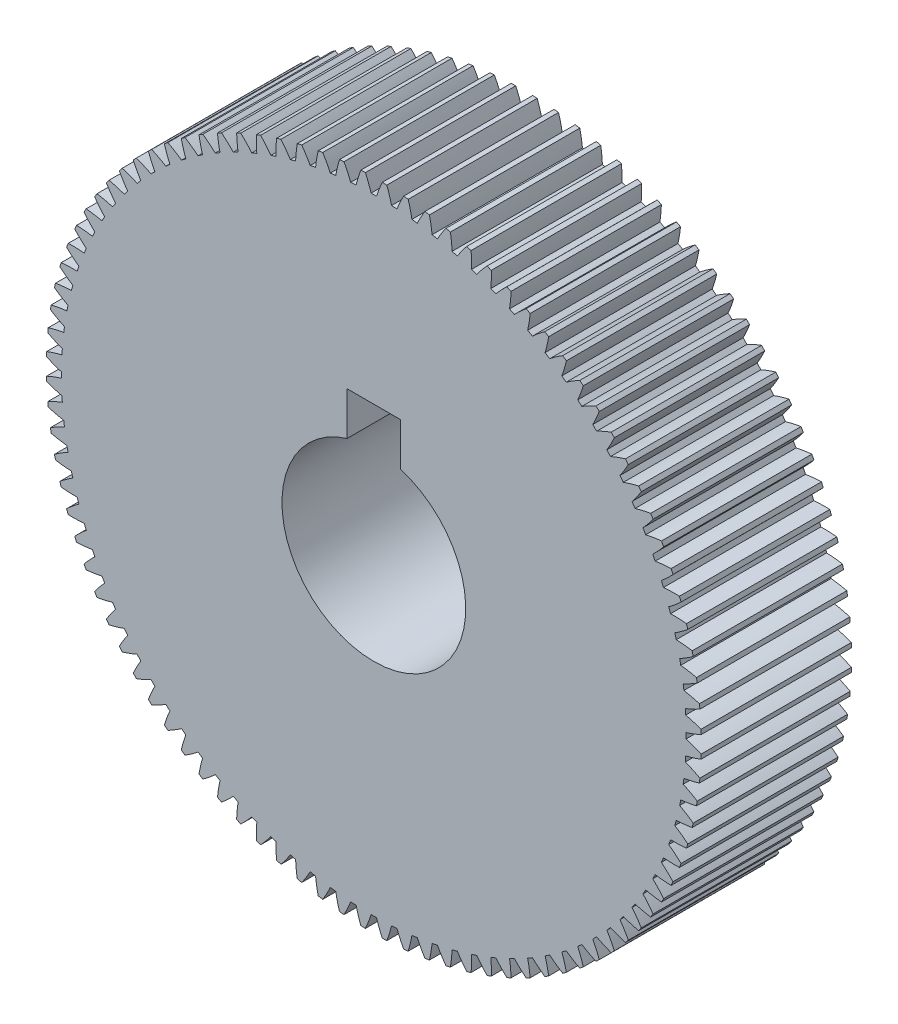
SolidWorks part; units mm, degrees
ref_plane "前视基准面" through (0, 0, 0) normal (0, 0, 1) x (1, 0, 0)
ref_plane "上视基准面" through (0, 0, 0) normal (0, 1, 0) x (1, 0, 0)
ref_plane "右视基准面" through (0, 0, 0) normal (1, 0, 0) x (0, 0, -1)
sketch "Model" plane through (0, 0, 0) normal (0, 0, 1) x (1, 0, 0)
  line L0 (6, 19.0788) -> (6, 23.3)
  line L1 (-6, 23.3) -> (-6, 19.0788)
  line L2 (6, 23.3) -> (-6, 23.3)
  arc A0 (-97.9675, 2.5241) -> (-93.4954, 0.8163) centre (-82.0589, 37.4737) ccw
  arc A1 (-93.4954, 0.8163) -> (-93.4954, -0.8163) centre (0, 0) ccw
  arc A2 (-93.4954, -0.8163) -> (-97.9675, -2.5241) centre (-82.0589, -37.4737) ccw
  arc A3 (-97.9675, -2.5241) -> (-97.9228, -3.8887) centre (0, 0) ccw
  arc A4 (-97.9228, -3.8887) -> (-93.3486, -5.3003) centre (-84.3341, 32.0266) ccw
  arc A5 (-93.3486, -5.3003) -> (-93.2419, -6.9294) centre (0, 0) ccw
  arc A6 (-93.2419, -6.9294) -> (-97.5927, -8.9261) centre (-79.4323, -42.7604) ccw
  arc A7 (-97.5927, -8.9261) -> (-97.4588, -10.2848) centre (0, 0) ccw
  arc A8 (-97.4588, -10.2848) -> (-92.8021, -11.3943) centre (-86.2481, 26.4423) ccw
  arc A9 (-92.8021, -11.3943) -> (-92.589, -13.0129) centre (0, 0) ccw
  arc A10 (-92.589, -13.0129) -> (-96.7999, -15.2898) centre (-76.4655, -47.8639) ccw
  arc A11 (-96.7999, -15.2898) -> (-96.5775, -16.6369) centre (0, 0) ccw
  arc A12 (-96.5775, -16.6369) -> (-91.8582, -17.4394) centre (-87.7929, 20.7448) ccw
  arc A13 (-91.8582, -17.4394) -> (-91.5397, -19.0407) centre (0, 0) ccw
  arc A14 (-91.5397, -19.0407) -> (-95.5926, -21.5881) centre (-73.1714, -52.7625) ccw
  arc A15 (-95.5926, -21.5881) -> (-95.2826, -22.9178) centre (0, 0) ccw
  arc A16 (-95.2826, -22.9178) -> (-90.5209, -23.4099) centre (-88.9617, 14.9584) ccw
  arc A17 (-90.5209, -23.4099) -> (-90.0984, -24.9869) centre (0, 0) ccw
  arc A18 (-90.0984, -24.9869) -> (-93.976, -27.7939) centre (-69.5639, -57.4352) ccw
  arc A19 (-93.976, -27.7939) -> (-93.5797, -29.1005) centre (0, 0) ccw
  arc A20 (-93.5797, -29.1005) -> (-88.796, -29.2801) centre (-89.7495, 9.108) ccw
  arc A21 (-88.796, -29.2801) -> (-88.2713, -30.8261) centre (0, 0) ccw
  arc A22 (-88.2713, -30.8261) -> (-91.957, -33.8808) centre (-65.6585, -61.8619) ccw
  arc A23 (-91.957, -33.8808) -> (-91.4761, -35.1586) centre (0, 0) ccw
  arc A24 (-91.4761, -35.1586) -> (-86.6909, -35.025) centre (-90.1531, 3.2186) ccw
  arc A25 (-86.6909, -35.025) -> (-86.0661, -36.5333) centre (0, 0) ccw
  arc A26 (-86.0661, -36.5333) -> (-89.5442, -39.8225) centre (-61.4719, -66.0237) ccw
  arc A27 (-89.5442, -39.8225) -> (-88.9807, -41.0661) centre (0, 0) ccw
  arc A28 (-88.9807, -41.0661) -> (-84.2145, -40.6199) centre (-90.1705, -2.6846) ccw
  arc A29 (-84.2145, -40.6199) -> (-83.4925, -42.0841) centre (0, 0) ccw
  arc A30 (-83.4925, -42.0841) -> (-86.748, -45.5937) centre (-57.0222, -69.9028) ccw
  arc A31 (-86.748, -45.5937) -> (-86.1044, -46.7978) centre (0, 0) ccw
  arc A32 (-86.1044, -46.7978) -> (-81.3776, -46.0408) centre (-89.8019, -8.5763) ccw
  arc A33 (-81.3776, -46.0408) -> (-80.5613, -47.4547) centre (0, 0) ccw
  arc A34 (-80.5613, -47.4547) -> (-83.5803, -51.1697) centre (-52.3282, -73.4826) ccw
  arc A35 (-83.5803, -51.1697) -> (-82.8593, -52.3291) centre (0, 0) ccw
  arc A36 (-82.8593, -52.3291) -> (-78.1921, -51.2646) centre (-89.0487, -14.4312) ccw
  arc A37 (-78.1921, -51.2646) -> (-77.2851, -52.622) centre (0, 0) ccw
  arc A38 (-77.2851, -52.622) -> (-80.0547, -56.5265) centre (-47.4102, -76.7477) ccw
  arc A39 (-80.0547, -56.5265) -> (-79.2594, -57.6363) centre (0, 0) ccw
  arc A40 (-79.2594, -57.6363) -> (-74.6719, -56.2688) centre (-87.9142, -20.2244) ccw
  arc A41 (-74.6719, -56.2688) -> (-73.678, -57.564) centre (0, 0) ccw
  arc A42 (-73.678, -57.564) -> (-76.1863, -61.6413) centre (-42.2891, -79.6841) ccw
  arc A43 (-76.1863, -61.6413) -> (-75.3201, -62.6967) centre (0, 0) ccw
  arc A44 (-75.3201, -62.6967) -> (-70.8318, -61.0321) centre (-86.4032, -25.9309) ccw
  arc A45 (-70.8318, -61.0321) -> (-69.7554, -62.2596) centre (0, 0) ccw
  arc A46 (-69.7554, -62.2596) -> (-71.9916, -66.4922) centre (-36.987, -82.2794) ccw
  arc A47 (-71.9916, -66.4922) -> (-71.0583, -67.4887) centre (0, 0) ccw
  arc A48 (-71.0583, -67.4887) -> (-66.6885, -65.534) centre (-84.5223, -31.5265) ccw
  arc A49 (-66.6885, -65.534) -> (-65.534, -66.6885) centre (0, 0) ccw
  arc A50 (-65.534, -66.6885) -> (-67.4887, -71.0583) centre (-31.5265, -84.5223) ccw
  arc A51 (-67.4887, -71.0583) -> (-66.4922, -71.9916) centre (0, 0) ccw
  arc A52 (-66.4922, -71.9916) -> (-62.2596, -69.7554) centre (-82.2794, -36.987) ccw
  arc A53 (-62.2596, -69.7554) -> (-61.0321, -70.8318) centre (0, 0) ccw
  arc A54 (-61.0321, -70.8318) -> (-62.6967, -75.3201) centre (-25.9309, -86.4032) ccw
  arc A55 (-62.6967, -75.3201) -> (-61.6413, -76.1863) centre (0, 0) ccw
  arc A56 (-61.6413, -76.1863) -> (-57.564, -73.678) centre (-79.6841, -42.2891) ccw
  arc A57 (-57.564, -73.678) -> (-56.2688, -74.6719) centre (0, 0) ccw
  arc A58 (-56.2688, -74.6719) -> (-57.6363, -79.2594) centre (-20.2244, -87.9142) ccw
  arc A59 (-57.6363, -79.2594) -> (-56.5265, -80.0547) centre (0, 0) ccw
  arc A60 (-56.5265, -80.0547) -> (-52.622, -77.2851) centre (-76.7477, -47.4102) ccw
  arc A61 (-52.622, -77.2851) -> (-51.2646, -78.1921) centre (0, 0) ccw
  arc A62 (-51.2646, -78.1921) -> (-52.3291, -82.8593) centre (-14.4312, -89.0487) ccw
  arc A63 (-52.3291, -82.8593) -> (-51.1697, -83.5803) centre (0, 0) ccw
  arc A64 (-51.1697, -83.5803) -> (-47.4547, -80.5613) centre (-73.4826, -52.3282) ccw
  arc A65 (-47.4547, -80.5613) -> (-46.0408, -81.3776) centre (0, 0) ccw
  arc A66 (-46.0408, -81.3776) -> (-46.7978, -86.1044) centre (-8.5763, -89.8019) ccw
  arc A67 (-46.7978, -86.1044) -> (-45.5937, -86.748) centre (0, 0) ccw
  arc A68 (-45.5937, -86.748) -> (-42.0841, -83.4925) centre (-69.9028, -57.0222) ccw
  arc A69 (-42.0841, -83.4925) -> (-40.6199, -84.2145) centre (0, 0) ccw
  arc A70 (-40.6199, -84.2145) -> (-41.0661, -88.9807) centre (-2.6846, -90.1705) ccw
  arc A71 (-41.0661, -88.9807) -> (-39.8225, -89.5442) centre (0, 0) ccw
  arc A72 (-39.8225, -89.5442) -> (-36.5333, -86.0661) centre (-66.0237, -61.4719) ccw
  arc A73 (-36.5333, -86.0661) -> (-35.025, -86.6909) centre (0, 0) ccw
  arc A74 (-35.025, -86.6909) -> (-35.1586, -91.4761) centre (3.2186, -90.1531) ccw
  arc A75 (-35.1586, -91.4761) -> (-33.8808, -91.957) centre (0, 0) ccw
  arc A76 (-33.8808, -91.957) -> (-30.8261, -88.2713) centre (-61.8619, -65.6585) ccw
  arc A77 (-30.8261, -88.2713) -> (-29.2801, -88.796) centre (0, 0) ccw
  arc A78 (-29.2801, -88.796) -> (-29.1005, -93.5797) centre (9.108, -89.7495) ccw
  arc A79 (-29.1005, -93.5797) -> (-27.7939, -93.976) centre (0, 0) ccw
  arc A80 (-27.7939, -93.976) -> (-24.9869, -90.0984) centre (-57.4352, -69.5639) ccw
  arc A81 (-24.9869, -90.0984) -> (-23.4099, -90.5209) centre (0, 0) ccw
  arc A82 (-23.4099, -90.5209) -> (-22.9178, -95.2826) centre (14.9584, -88.9617) ccw
  arc A83 (-22.9178, -95.2826) -> (-21.5881, -95.5926) centre (0, 0) ccw
  arc A84 (-21.5881, -95.5926) -> (-19.0407, -91.5397) centre (-52.7625, -73.1714) ccw
  arc A85 (-19.0407, -91.5397) -> (-17.4394, -91.8582) centre (0, 0) ccw
  arc A86 (-17.4394, -91.8582) -> (-16.6369, -96.5775) centre (20.7448, -87.7929) ccw
  arc A87 (-16.6369, -96.5775) -> (-15.2898, -96.7999) centre (0, 0) ccw
  arc A88 (-15.2898, -96.7999) -> (-13.0129, -92.589) centre (-47.8639, -76.4655) ccw
  arc A89 (-13.0129, -92.589) -> (-11.3943, -92.8021) centre (0, 0) ccw
  arc A90 (-11.3943, -92.8021) -> (-10.2848, -97.4588) centre (26.4423, -86.2481) ccw
  arc A91 (-10.2848, -97.4588) -> (-8.9261, -97.5927) centre (0, 0) ccw
  arc A92 (-8.9261, -97.5927) -> (-6.9294, -93.2419) centre (-42.7604, -79.4323) ccw
  arc A93 (-6.9294, -93.2419) -> (-5.3003, -93.3486) centre (0, 0) ccw
  arc A94 (-5.3003, -93.3486) -> (-3.8887, -97.9228) centre (32.0266, -84.3341) ccw
  arc A95 (-3.8887, -97.9228) -> (-2.5241, -97.9675) centre (0, 0) ccw
  arc A96 (-2.5241, -97.9675) -> (-0.8163, -93.4954) centre (-37.4737, -82.0589) ccw
  arc A97 (-0.8163, -93.4954) -> (0.8163, -93.4954) centre (0, 0) ccw
  arc A98 (0.8163, -93.4954) -> (2.5241, -97.9675) centre (37.4737, -82.0589) ccw
  arc A99 (2.5241, -97.9675) -> (3.8887, -97.9228) centre (0, 0) ccw
  arc A100 (3.8887, -97.9228) -> (5.3003, -93.3486) centre (-32.0266, -84.3341) ccw
  arc A101 (5.3003, -93.3486) -> (6.9294, -93.2419) centre (0, 0) ccw
  arc A102 (6.9294, -93.2419) -> (8.9261, -97.5927) centre (42.7604, -79.4323) ccw
  arc A103 (8.9261, -97.5927) -> (10.2848, -97.4588) centre (0, 0) ccw
  arc A104 (10.2848, -97.4588) -> (11.3943, -92.8021) centre (-26.4423, -86.2481) ccw
  arc A105 (11.3943, -92.8021) -> (13.0129, -92.589) centre (0, 0) ccw
  arc A106 (13.0129, -92.589) -> (15.2898, -96.7999) centre (47.8639, -76.4655) ccw
  arc A107 (15.2898, -96.7999) -> (16.6369, -96.5775) centre (0, 0) ccw
  arc A108 (16.6369, -96.5775) -> (17.4394, -91.8582) centre (-20.7448, -87.7929) ccw
  arc A109 (17.4394, -91.8582) -> (19.0407, -91.5397) centre (0, 0) ccw
  arc A110 (19.0407, -91.5397) -> (21.5881, -95.5926) centre (52.7625, -73.1714) ccw
  arc A111 (21.5881, -95.5926) -> (22.9178, -95.2826) centre (0, 0) ccw
  arc A112 (22.9178, -95.2826) -> (23.4099, -90.5209) centre (-14.9584, -88.9617) ccw
  arc A113 (23.4099, -90.5209) -> (24.9869, -90.0984) centre (0, 0) ccw
  arc A114 (24.9869, -90.0984) -> (27.7939, -93.976) centre (57.4352, -69.5639) ccw
  arc A115 (27.7939, -93.976) -> (29.1005, -93.5797) centre (0, 0) ccw
  arc A116 (29.1005, -93.5797) -> (29.2801, -88.796) centre (-9.108, -89.7495) ccw
  arc A117 (29.2801, -88.796) -> (30.8261, -88.2713) centre (0, 0) ccw
  arc A118 (30.8261, -88.2713) -> (33.8808, -91.957) centre (61.8619, -65.6585) ccw
  arc A119 (33.8808, -91.957) -> (35.1586, -91.4761) centre (0, 0) ccw
  arc A120 (35.1586, -91.4761) -> (35.025, -86.6909) centre (-3.2186, -90.1531) ccw
  arc A121 (35.025, -86.6909) -> (36.5333, -86.0661) centre (0, 0) ccw
  arc A122 (36.5333, -86.0661) -> (39.8225, -89.5442) centre (66.0237, -61.4719) ccw
  arc A123 (39.8225, -89.5442) -> (41.0661, -88.9807) centre (0, 0) ccw
  arc A124 (41.0661, -88.9807) -> (40.6199, -84.2145) centre (2.6846, -90.1705) ccw
  arc A125 (40.6199, -84.2145) -> (42.0841, -83.4925) centre (0, 0) ccw
  arc A126 (42.0841, -83.4925) -> (45.5937, -86.748) centre (69.9028, -57.0222) ccw
  arc A127 (45.5937, -86.748) -> (46.7978, -86.1044) centre (0, 0) ccw
  arc A128 (46.7978, -86.1044) -> (46.0408, -81.3776) centre (8.5763, -89.8019) ccw
  arc A129 (46.0408, -81.3776) -> (47.4547, -80.5613) centre (0, 0) ccw
  arc A130 (47.4547, -80.5613) -> (51.1697, -83.5803) centre (73.4826, -52.3282) ccw
  arc A131 (51.1697, -83.5803) -> (52.3291, -82.8593) centre (0, 0) ccw
  arc A132 (52.3291, -82.8593) -> (51.2646, -78.1921) centre (14.4312, -89.0487) ccw
  arc A133 (51.2646, -78.1921) -> (52.622, -77.2851) centre (0, 0) ccw
  arc A134 (52.622, -77.2851) -> (56.5265, -80.0547) centre (76.7477, -47.4102) ccw
  arc A135 (56.5265, -80.0547) -> (57.6363, -79.2594) centre (0, 0) ccw
  arc A136 (57.6363, -79.2594) -> (56.2688, -74.6719) centre (20.2244, -87.9142) ccw
  arc A137 (56.2688, -74.6719) -> (57.564, -73.678) centre (0, 0) ccw
  arc A138 (57.564, -73.678) -> (61.6413, -76.1863) centre (79.6841, -42.2891) ccw
  arc A139 (61.6413, -76.1863) -> (62.6967, -75.3201) centre (0, 0) ccw
  arc A140 (62.6967, -75.3201) -> (61.0321, -70.8318) centre (25.9309, -86.4032) ccw
  arc A141 (61.0321, -70.8318) -> (62.2596, -69.7554) centre (0, 0) ccw
  arc A142 (62.2596, -69.7554) -> (66.4922, -71.9916) centre (82.2794, -36.987) ccw
  arc A143 (66.4922, -71.9916) -> (67.4887, -71.0583) centre (0, 0) ccw
  arc A144 (67.4887, -71.0583) -> (65.534, -66.6885) centre (31.5265, -84.5223) ccw
  arc A145 (65.534, -66.6885) -> (66.6885, -65.534) centre (0, 0) ccw
  arc A146 (66.6885, -65.534) -> (71.0583, -67.4887) centre (84.5223, -31.5265) ccw
  arc A147 (71.0583, -67.4887) -> (71.9916, -66.4922) centre (0, 0) ccw
  arc A148 (71.9916, -66.4922) -> (69.7554, -62.2596) centre (36.987, -82.2794) ccw
  arc A149 (69.7554, -62.2596) -> (70.8318, -61.0321) centre (0, 0) ccw
  arc A150 (70.8318, -61.0321) -> (75.3201, -62.6967) centre (86.4032, -25.9309) ccw
  arc A151 (75.3201, -62.6967) -> (76.1863, -61.6413) centre (0, 0) ccw
  arc A152 (76.1863, -61.6413) -> (73.678, -57.564) centre (42.2891, -79.6841) ccw
  arc A153 (73.678, -57.564) -> (74.6719, -56.2688) centre (0, 0) ccw
  arc A154 (74.6719, -56.2688) -> (79.2594, -57.6363) centre (87.9142, -20.2244) ccw
  arc A155 (79.2594, -57.6363) -> (80.0547, -56.5265) centre (0, 0) ccw
  arc A156 (80.0547, -56.5265) -> (77.2851, -52.622) centre (47.4102, -76.7477) ccw
  arc A157 (77.2851, -52.622) -> (78.1921, -51.2646) centre (0, 0) ccw
  arc A158 (78.1921, -51.2646) -> (82.8593, -52.3291) centre (89.0487, -14.4312) ccw
  arc A159 (82.8593, -52.3291) -> (83.5803, -51.1697) centre (0, 0) ccw
  arc A160 (83.5803, -51.1697) -> (80.5613, -47.4547) centre (52.3282, -73.4826) ccw
  arc A161 (80.5613, -47.4547) -> (81.3776, -46.0408) centre (0, 0) ccw
  arc A162 (81.3776, -46.0408) -> (86.1044, -46.7978) centre (89.8019, -8.5763) ccw
  arc A163 (86.1044, -46.7978) -> (86.748, -45.5937) centre (0, 0) ccw
  arc A164 (86.748, -45.5937) -> (83.4925, -42.0841) centre (57.0222, -69.9028) ccw
  arc A165 (83.4925, -42.0841) -> (84.2145, -40.6199) centre (0, 0) ccw
  arc A166 (84.2145, -40.6199) -> (88.9807, -41.0661) centre (90.1705, -2.6846) ccw
  arc A167 (88.9807, -41.0661) -> (89.5442, -39.8225) centre (0, 0) ccw
  arc A168 (89.5442, -39.8225) -> (86.0661, -36.5333) centre (61.4719, -66.0237) ccw
  arc A169 (86.0661, -36.5333) -> (86.6909, -35.025) centre (0, 0) ccw
  arc A170 (86.6909, -35.025) -> (91.4761, -35.1586) centre (90.1531, 3.2186) ccw
  arc A171 (91.4761, -35.1586) -> (91.957, -33.8808) centre (0, 0) ccw
  arc A172 (91.957, -33.8808) -> (88.2713, -30.8261) centre (65.6585, -61.8619) ccw
  arc A173 (88.2713, -30.8261) -> (88.796, -29.2801) centre (0, 0) ccw
  arc A174 (88.796, -29.2801) -> (93.5797, -29.1005) centre (89.7495, 9.108) ccw
  arc A175 (93.5797, -29.1005) -> (93.976, -27.7939) centre (0, 0) ccw
  arc A176 (93.976, -27.7939) -> (90.0984, -24.9869) centre (69.5639, -57.4352) ccw
  arc A177 (90.0984, -24.9869) -> (90.5209, -23.4099) centre (0, 0) ccw
  arc A178 (90.5209, -23.4099) -> (95.2826, -22.9178) centre (88.9617, 14.9584) ccw
  arc A179 (95.2826, -22.9178) -> (95.5926, -21.5881) centre (0, 0) ccw
  arc A180 (95.5926, -21.5881) -> (91.5397, -19.0407) centre (73.1714, -52.7625) ccw
  arc A181 (91.5397, -19.0407) -> (91.8582, -17.4394) centre (0, 0) ccw
  arc A182 (91.8582, -17.4394) -> (96.5775, -16.6369) centre (87.7929, 20.7448) ccw
  arc A183 (96.5775, -16.6369) -> (96.7999, -15.2898) centre (0, 0) ccw
  arc A184 (96.7999, -15.2898) -> (92.589, -13.0129) centre (76.4655, -47.8639) ccw
  arc A185 (92.589, -13.0129) -> (92.8021, -11.3943) centre (0, 0) ccw
  arc A186 (92.8021, -11.3943) -> (97.4588, -10.2848) centre (86.2481, 26.4423) ccw
  arc A187 (97.4588, -10.2848) -> (97.5927, -8.9261) centre (0, 0) ccw
  arc A188 (97.5927, -8.9261) -> (93.2419, -6.9294) centre (79.4323, -42.7604) ccw
  arc A189 (93.2419, -6.9294) -> (93.3486, -5.3003) centre (0, 0) ccw
  arc A190 (93.3486, -5.3003) -> (97.9228, -3.8887) centre (84.3341, 32.0266) ccw
  arc A191 (97.9228, -3.8887) -> (97.9675, -2.5241) centre (0, 0) ccw
  arc A192 (97.9675, -2.5241) -> (93.4954, -0.8163) centre (82.0589, -37.4737) ccw
  arc A193 (93.4954, -0.8163) -> (93.4954, 0.8163) centre (0, 0) ccw
  arc A194 (93.4954, 0.8163) -> (97.9675, 2.5241) centre (82.0589, 37.4737) ccw
  arc A195 (97.9675, 2.5241) -> (97.9228, 3.8887) centre (0, 0) ccw
  arc A196 (97.9228, 3.8887) -> (93.3486, 5.3003) centre (84.3341, -32.0266) ccw
  arc A197 (93.3486, 5.3003) -> (93.2419, 6.9294) centre (0, 0) ccw
  arc A198 (93.2419, 6.9294) -> (97.5927, 8.9261) centre (79.4323, 42.7604) ccw
  arc A199 (97.5927, 8.9261) -> (97.4588, 10.2848) centre (0, 0) ccw
  arc A200 (97.4588, 10.2848) -> (92.8021, 11.3943) centre (86.2481, -26.4423) ccw
  arc A201 (92.8021, 11.3943) -> (92.589, 13.0129) centre (0, 0) ccw
  arc A202 (92.589, 13.0129) -> (96.7999, 15.2898) centre (76.4655, 47.8639) ccw
  arc A203 (96.7999, 15.2898) -> (96.5775, 16.6369) centre (0, 0) ccw
  arc A204 (96.5775, 16.6369) -> (91.8582, 17.4394) centre (87.7929, -20.7448) ccw
  arc A205 (91.8582, 17.4394) -> (91.5397, 19.0407) centre (0, 0) ccw
  arc A206 (91.5397, 19.0407) -> (95.5926, 21.5881) centre (73.1714, 52.7625) ccw
  arc A207 (95.5926, 21.5881) -> (95.2826, 22.9178) centre (0, 0) ccw
  arc A208 (95.2826, 22.9178) -> (90.5209, 23.4099) centre (88.9617, -14.9584) ccw
  arc A209 (90.5209, 23.4099) -> (90.0984, 24.9869) centre (0, 0) ccw
  arc A210 (90.0984, 24.9869) -> (93.976, 27.7939) centre (69.5639, 57.4352) ccw
  arc A211 (93.976, 27.7939) -> (93.5797, 29.1005) centre (0, 0) ccw
  arc A212 (93.5797, 29.1005) -> (88.796, 29.2801) centre (89.7495, -9.108) ccw
  arc A213 (88.796, 29.2801) -> (88.2713, 30.8261) centre (0, 0) ccw
  arc A214 (88.2713, 30.8261) -> (91.957, 33.8808) centre (65.6585, 61.8619) ccw
  arc A215 (91.957, 33.8808) -> (91.4761, 35.1586) centre (0, 0) ccw
  arc A216 (91.4761, 35.1586) -> (86.6909, 35.025) centre (90.1531, -3.2186) ccw
  arc A217 (86.6909, 35.025) -> (86.0661, 36.5333) centre (0, 0) ccw
  arc A218 (86.0661, 36.5333) -> (89.5442, 39.8225) centre (61.4719, 66.0237) ccw
  arc A219 (89.5442, 39.8225) -> (88.9807, 41.0661) centre (0, 0) ccw
  arc A220 (88.9807, 41.0661) -> (84.2145, 40.6199) centre (90.1705, 2.6846) ccw
  arc A221 (84.2145, 40.6199) -> (83.4925, 42.0841) centre (0, 0) ccw
  arc A222 (83.4925, 42.0841) -> (86.748, 45.5937) centre (57.0222, 69.9028) ccw
  arc A223 (86.748, 45.5937) -> (86.1044, 46.7978) centre (0, 0) ccw
  arc A224 (86.1044, 46.7978) -> (81.3776, 46.0408) centre (89.8019, 8.5763) ccw
  arc A225 (81.3776, 46.0408) -> (80.5613, 47.4547) centre (0, 0) ccw
  arc A226 (80.5613, 47.4547) -> (83.5803, 51.1697) centre (52.3282, 73.4826) ccw
  arc A227 (83.5803, 51.1697) -> (82.8593, 52.3291) centre (0, 0) ccw
  arc A228 (82.8593, 52.3291) -> (78.1921, 51.2646) centre (89.0487, 14.4312) ccw
  arc A229 (78.1921, 51.2646) -> (77.2851, 52.622) centre (0, 0) ccw
  arc A230 (77.2851, 52.622) -> (80.0547, 56.5265) centre (47.4102, 76.7477) ccw
  arc A231 (80.0547, 56.5265) -> (79.2594, 57.6363) centre (0, 0) ccw
  arc A232 (79.2594, 57.6363) -> (74.6719, 56.2688) centre (87.9142, 20.2244) ccw
  arc A233 (74.6719, 56.2688) -> (73.678, 57.564) centre (0, 0) ccw
  arc A234 (73.678, 57.564) -> (76.1863, 61.6413) centre (42.2891, 79.6841) ccw
  arc A235 (76.1863, 61.6413) -> (75.3201, 62.6967) centre (0, 0) ccw
  arc A236 (75.3201, 62.6967) -> (70.8318, 61.0321) centre (86.4032, 25.9309) ccw
  arc A237 (70.8318, 61.0321) -> (69.7554, 62.2596) centre (0, 0) ccw
  arc A238 (69.7554, 62.2596) -> (71.9916, 66.4922) centre (36.987, 82.2794) ccw
  arc A239 (71.9916, 66.4922) -> (71.0583, 67.4887) centre (0, 0) ccw
  arc A240 (71.0583, 67.4887) -> (66.6885, 65.534) centre (84.5223, 31.5265) ccw
  arc A241 (66.6885, 65.534) -> (65.534, 66.6885) centre (0, 0) ccw
  arc A242 (65.534, 66.6885) -> (67.4887, 71.0583) centre (31.5265, 84.5223) ccw
  arc A243 (67.4887, 71.0583) -> (66.4922, 71.9916) centre (0, 0) ccw
  arc A244 (66.4922, 71.9916) -> (62.2596, 69.7554) centre (82.2794, 36.987) ccw
  arc A245 (62.2596, 69.7554) -> (61.0321, 70.8318) centre (0, 0) ccw
  arc A246 (61.0321, 70.8318) -> (62.6967, 75.3201) centre (25.9309, 86.4032) ccw
  arc A247 (62.6967, 75.3201) -> (61.6413, 76.1863) centre (0, 0) ccw
  arc A248 (61.6413, 76.1863) -> (57.564, 73.678) centre (79.6841, 42.2891) ccw
  arc A249 (57.564, 73.678) -> (56.2688, 74.6719) centre (0, 0) ccw
  arc A250 (56.2688, 74.6719) -> (57.6363, 79.2594) centre (20.2244, 87.9142) ccw
  arc A251 (57.6363, 79.2594) -> (56.5265, 80.0547) centre (0, 0) ccw
  arc A252 (56.5265, 80.0547) -> (52.622, 77.2851) centre (76.7477, 47.4102) ccw
  arc A253 (52.622, 77.2851) -> (51.2646, 78.1921) centre (0, 0) ccw
  arc A254 (51.2646, 78.1921) -> (52.3291, 82.8593) centre (14.4312, 89.0487) ccw
  arc A255 (52.3291, 82.8593) -> (51.1697, 83.5803) centre (0, 0) ccw
  arc A256 (51.1697, 83.5803) -> (47.4547, 80.5613) centre (73.4826, 52.3282) ccw
  arc A257 (47.4547, 80.5613) -> (46.0408, 81.3776) centre (0, 0) ccw
  arc A258 (46.0408, 81.3776) -> (46.7978, 86.1044) centre (8.5763, 89.8019) ccw
  arc A259 (46.7978, 86.1044) -> (45.5937, 86.748) centre (0, 0) ccw
  arc A260 (45.5937, 86.748) -> (42.0841, 83.4925) centre (69.9028, 57.0222) ccw
  arc A261 (42.0841, 83.4925) -> (40.6199, 84.2145) centre (0, 0) ccw
  arc A262 (40.6199, 84.2145) -> (41.0661, 88.9807) centre (2.6846, 90.1705) ccw
  arc A263 (41.0661, 88.9807) -> (39.8225, 89.5442) centre (0, 0) ccw
  arc A264 (39.8225, 89.5442) -> (36.5333, 86.0661) centre (66.0237, 61.4719) ccw
  arc A265 (36.5333, 86.0661) -> (35.025, 86.6909) centre (0, 0) ccw
  arc A266 (35.025, 86.6909) -> (35.1586, 91.4761) centre (-3.2186, 90.1531) ccw
  arc A267 (35.1586, 91.4761) -> (33.8808, 91.957) centre (0, 0) ccw
  arc A268 (33.8808, 91.957) -> (30.8261, 88.2713) centre (61.8619, 65.6585) ccw
  arc A269 (30.8261, 88.2713) -> (29.2801, 88.796) centre (0, 0) ccw
  arc A270 (29.2801, 88.796) -> (29.1005, 93.5797) centre (-9.108, 89.7495) ccw
  arc A271 (29.1005, 93.5797) -> (27.7939, 93.976) centre (0, 0) ccw
  arc A272 (27.7939, 93.976) -> (24.9869, 90.0984) centre (57.4352, 69.5639) ccw
  arc A273 (24.9869, 90.0984) -> (23.4099, 90.5209) centre (0, 0) ccw
  arc A274 (23.4099, 90.5209) -> (22.9178, 95.2826) centre (-14.9584, 88.9617) ccw
  arc A275 (22.9178, 95.2826) -> (21.5881, 95.5926) centre (0, 0) ccw
  arc A276 (21.5881, 95.5926) -> (19.0407, 91.5397) centre (52.7625, 73.1714) ccw
  arc A277 (19.0407, 91.5397) -> (17.4394, 91.8582) centre (0, 0) ccw
  arc A278 (17.4394, 91.8582) -> (16.6369, 96.5775) centre (-20.7448, 87.7929) ccw
  arc A279 (16.6369, 96.5775) -> (15.2898, 96.7999) centre (0, 0) ccw
  arc A280 (15.2898, 96.7999) -> (13.0129, 92.589) centre (47.8639, 76.4655) ccw
  arc A281 (13.0129, 92.589) -> (11.3943, 92.8021) centre (0, 0) ccw
  arc A282 (11.3943, 92.8021) -> (10.2848, 97.4588) centre (-26.4423, 86.2481) ccw
  arc A283 (10.2848, 97.4588) -> (8.9261, 97.5927) centre (0, 0) ccw
  arc A284 (8.9261, 97.5927) -> (6.9294, 93.2419) centre (42.7604, 79.4323) ccw
  arc A285 (6.9294, 93.2419) -> (5.3003, 93.3486) centre (0, 0) ccw
  arc A286 (5.3003, 93.3486) -> (3.8887, 97.9228) centre (-32.0266, 84.3341) ccw
  arc A287 (3.8887, 97.9228) -> (2.5241, 97.9675) centre (0, 0) ccw
  arc A288 (2.5241, 97.9675) -> (0.8163, 93.4954) centre (37.4737, 82.0589) ccw
  arc A289 (0.8163, 93.4954) -> (-0.8163, 93.4954) centre (0, 0) ccw
  arc A290 (-0.8163, 93.4954) -> (-2.5241, 97.9675) centre (-37.4737, 82.0589) ccw
  arc A291 (-2.5241, 97.9675) -> (-3.8887, 97.9228) centre (0, 0) ccw
  arc A292 (-3.8887, 97.9228) -> (-5.3003, 93.3486) centre (32.0266, 84.3341) ccw
  arc A293 (-5.3003, 93.3486) -> (-6.9294, 93.2419) centre (0, 0) ccw
  arc A294 (-6.9294, 93.2419) -> (-8.9261, 97.5927) centre (-42.7604, 79.4323) ccw
  arc A295 (-8.9261, 97.5927) -> (-10.2848, 97.4588) centre (0, 0) ccw
  arc A296 (-10.2848, 97.4588) -> (-11.3943, 92.8021) centre (26.4423, 86.2481) ccw
  arc A297 (-11.3943, 92.8021) -> (-13.0129, 92.589) centre (0, 0) ccw
  arc A298 (-13.0129, 92.589) -> (-15.2898, 96.7999) centre (-47.8639, 76.4655) ccw
  arc A299 (-15.2898, 96.7999) -> (-16.6369, 96.5775) centre (0, 0) ccw
  arc A300 (-16.6369, 96.5775) -> (-17.4394, 91.8582) centre (20.7448, 87.7929) ccw
  arc A301 (-17.4394, 91.8582) -> (-19.0407, 91.5397) centre (0, 0) ccw
  arc A302 (-19.0407, 91.5397) -> (-21.5881, 95.5926) centre (-52.7625, 73.1714) ccw
  arc A303 (-21.5881, 95.5926) -> (-22.9178, 95.2826) centre (0, 0) ccw
  arc A304 (-22.9178, 95.2826) -> (-23.4099, 90.5209) centre (14.9584, 88.9617) ccw
  arc A305 (-23.4099, 90.5209) -> (-24.9869, 90.0984) centre (0, 0) ccw
  arc A306 (-24.9869, 90.0984) -> (-27.7939, 93.976) centre (-57.4352, 69.5639) ccw
  arc A307 (-27.7939, 93.976) -> (-29.1005, 93.5797) centre (0, 0) ccw
  arc A308 (-29.1005, 93.5797) -> (-29.2801, 88.796) centre (9.108, 89.7495) ccw
  arc A309 (-29.2801, 88.796) -> (-30.8261, 88.2713) centre (0, 0) ccw
  arc A310 (-30.8261, 88.2713) -> (-33.8808, 91.957) centre (-61.8619, 65.6585) ccw
  arc A311 (-33.8808, 91.957) -> (-35.1586, 91.4761) centre (0, 0) ccw
  arc A312 (-35.1586, 91.4761) -> (-35.025, 86.6909) centre (3.2186, 90.1531) ccw
  arc A313 (-35.025, 86.6909) -> (-36.5333, 86.0661) centre (0, 0) ccw
  arc A314 (-36.5333, 86.0661) -> (-39.8225, 89.5442) centre (-66.0237, 61.4719) ccw
  arc A315 (-39.8225, 89.5442) -> (-41.0661, 88.9807) centre (0, 0) ccw
  arc A316 (-41.0661, 88.9807) -> (-40.6199, 84.2145) centre (-2.6846, 90.1705) ccw
  arc A317 (-40.6199, 84.2145) -> (-42.0841, 83.4925) centre (0, 0) ccw
  arc A318 (-42.0841, 83.4925) -> (-45.5937, 86.748) centre (-69.9028, 57.0222) ccw
  arc A319 (-45.5937, 86.748) -> (-46.7978, 86.1044) centre (0, 0) ccw
  arc A320 (-46.7978, 86.1044) -> (-46.0408, 81.3776) centre (-8.5763, 89.8019) ccw
  arc A321 (-46.0408, 81.3776) -> (-47.4547, 80.5613) centre (0, 0) ccw
  arc A322 (-47.4547, 80.5613) -> (-51.1697, 83.5803) centre (-73.4826, 52.3282) ccw
  arc A323 (-51.1697, 83.5803) -> (-52.3291, 82.8593) centre (0, 0) ccw
  arc A324 (-52.3291, 82.8593) -> (-51.2646, 78.1921) centre (-14.4312, 89.0487) ccw
  arc A325 (-51.2646, 78.1921) -> (-52.622, 77.2851) centre (0, 0) ccw
  arc A326 (-52.622, 77.2851) -> (-56.5265, 80.0547) centre (-76.7477, 47.4102) ccw
  arc A327 (-56.5265, 80.0547) -> (-57.6363, 79.2594) centre (0, 0) ccw
  arc A328 (-57.6363, 79.2594) -> (-56.2688, 74.6719) centre (-20.2244, 87.9142) ccw
  arc A329 (-56.2688, 74.6719) -> (-57.564, 73.678) centre (0, 0) ccw
  arc A330 (-57.564, 73.678) -> (-61.6413, 76.1863) centre (-79.6841, 42.2891) ccw
  arc A331 (-61.6413, 76.1863) -> (-62.6967, 75.3201) centre (0, 0) ccw
  arc A332 (-62.6967, 75.3201) -> (-61.0321, 70.8318) centre (-25.9309, 86.4032) ccw
  arc A333 (-61.0321, 70.8318) -> (-62.2596, 69.7554) centre (0, 0) ccw
  arc A334 (-62.2596, 69.7554) -> (-66.4922, 71.9916) centre (-82.2794, 36.987) ccw
  arc A335 (-66.4922, 71.9916) -> (-67.4887, 71.0583) centre (0, 0) ccw
  arc A336 (-67.4887, 71.0583) -> (-65.534, 66.6885) centre (-31.5265, 84.5223) ccw
  arc A337 (-65.534, 66.6885) -> (-66.6885, 65.534) centre (0, 0) ccw
  arc A338 (-66.6885, 65.534) -> (-71.0583, 67.4887) centre (-84.5223, 31.5265) ccw
  arc A339 (-71.0583, 67.4887) -> (-71.9916, 66.4922) centre (0, 0) ccw
  arc A340 (-71.9916, 66.4922) -> (-69.7554, 62.2596) centre (-36.987, 82.2794) ccw
  arc A341 (-69.7554, 62.2596) -> (-70.8318, 61.0321) centre (0, 0) ccw
  arc A342 (-70.8318, 61.0321) -> (-75.3201, 62.6967) centre (-86.4032, 25.9309) ccw
  arc A343 (-75.3201, 62.6967) -> (-76.1863, 61.6413) centre (0, 0) ccw
  arc A344 (-76.1863, 61.6413) -> (-73.678, 57.564) centre (-42.2891, 79.6841) ccw
  arc A345 (-73.678, 57.564) -> (-74.6719, 56.2688) centre (0, 0) ccw
  arc A346 (-74.6719, 56.2688) -> (-79.2594, 57.6363) centre (-87.9142, 20.2244) ccw
  arc A347 (-79.2594, 57.6363) -> (-80.0547, 56.5265) centre (0, 0) ccw
  arc A348 (-80.0547, 56.5265) -> (-77.2851, 52.622) centre (-47.4102, 76.7477) ccw
  arc A349 (-77.2851, 52.622) -> (-78.1921, 51.2646) centre (0, 0) ccw
  arc A350 (-78.1921, 51.2646) -> (-82.8593, 52.3291) centre (-89.0487, 14.4312) ccw
  arc A351 (-82.8593, 52.3291) -> (-83.5803, 51.1697) centre (0, 0) ccw
  arc A352 (-83.5803, 51.1697) -> (-80.5613, 47.4547) centre (-52.3282, 73.4826) ccw
  arc A353 (-80.5613, 47.4547) -> (-81.3776, 46.0408) centre (0, 0) ccw
  arc A354 (-81.3776, 46.0408) -> (-86.1044, 46.7978) centre (-89.8019, 8.5763) ccw
  arc A355 (-86.1044, 46.7978) -> (-86.748, 45.5937) centre (0, 0) ccw
  arc A356 (-86.748, 45.5937) -> (-83.4925, 42.0841) centre (-57.0222, 69.9028) ccw
  arc A357 (-83.4925, 42.0841) -> (-84.2145, 40.6199) centre (0, 0) ccw
  arc A358 (-84.2145, 40.6199) -> (-88.9807, 41.0661) centre (-90.1705, 2.6846) ccw
  arc A359 (-88.9807, 41.0661) -> (-89.5442, 39.8225) centre (0, 0) ccw
  arc A360 (-89.5442, 39.8225) -> (-86.0661, 36.5333) centre (-61.4719, 66.0237) ccw
  arc A361 (-86.0661, 36.5333) -> (-86.6909, 35.025) centre (0, 0) ccw
  arc A362 (-86.6909, 35.025) -> (-91.4761, 35.1586) centre (-90.1531, -3.2186) ccw
  arc A363 (-91.4761, 35.1586) -> (-91.957, 33.8808) centre (0, 0) ccw
  arc A364 (-91.957, 33.8808) -> (-88.2713, 30.8261) centre (-65.6585, 61.8619) ccw
  arc A365 (-88.2713, 30.8261) -> (-88.796, 29.2801) centre (0, 0) ccw
  arc A366 (-88.796, 29.2801) -> (-93.5797, 29.1005) centre (-89.7495, -9.108) ccw
  arc A367 (-93.5797, 29.1005) -> (-93.976, 27.7939) centre (0, 0) ccw
  arc A368 (-93.976, 27.7939) -> (-90.0984, 24.9869) centre (-69.5639, 57.4352) ccw
  arc A369 (-90.0984, 24.9869) -> (-90.5209, 23.4099) centre (0, 0) ccw
  arc A370 (-90.5209, 23.4099) -> (-95.2826, 22.9178) centre (-88.9617, -14.9584) ccw
  arc A371 (-95.2826, 22.9178) -> (-95.5926, 21.5881) centre (0, 0) ccw
  arc A372 (-95.5926, 21.5881) -> (-91.5397, 19.0407) centre (-73.1714, 52.7625) ccw
  arc A373 (-91.5397, 19.0407) -> (-91.8582, 17.4394) centre (0, 0) ccw
  arc A374 (-91.8582, 17.4394) -> (-96.5775, 16.6369) centre (-87.7929, -20.7448) ccw
  arc A375 (-96.5775, 16.6369) -> (-96.7999, 15.2898) centre (0, 0) ccw
  arc A376 (-96.7999, 15.2898) -> (-92.589, 13.0129) centre (-76.4655, 47.8639) ccw
  arc A377 (-92.589, 13.0129) -> (-92.8021, 11.3943) centre (0, 0) ccw
  arc A378 (-92.8021, 11.3943) -> (-97.4588, 10.2848) centre (-86.2481, -26.4423) ccw
  arc A379 (-97.4588, 10.2848) -> (-97.5927, 8.9261) centre (0, 0) ccw
  arc A380 (-97.5927, 8.9261) -> (-93.2419, 6.9294) centre (-79.4323, 42.7604) ccw
  arc A381 (-93.2419, 6.9294) -> (-93.3486, 5.3003) centre (0, 0) ccw
  arc A382 (-93.3486, 5.3003) -> (-97.9228, 3.8887) centre (-84.3341, -32.0266) ccw
  arc A383 (-97.9228, 3.8887) -> (-97.9675, 2.5241) centre (0, 0) ccw
  arc A384 (-6, 19.0788) -> (6, 19.0788) centre (0, 0) ccw
extrude "凸台-拉伸1" add sketch "Model" along normal blind 45
sketch "草图1" plane through (0, 0, 45) normal (0, 0, 1) x (1, 0, 0)
  line L0 (0, 0) -> (0, 39.1952)
  line L1 (0, 39.1952) -> (-8, 39.1952)
  line L2 (0, 39.1952) -> (8, 39.1952)
  line L3 (-8, 39.1952) -> (-8, 26.3106)
  line L4 (8, 39.1952) -> (8, 26.3106)
  circle A0 centre (0, 0) radius 27.5
  dimension "D1" = 55
  dimension "D2" = 8
  dimension "D3" = 8
extrude "切除-拉伸1" cut sketch "草图1" against normal blind 96
